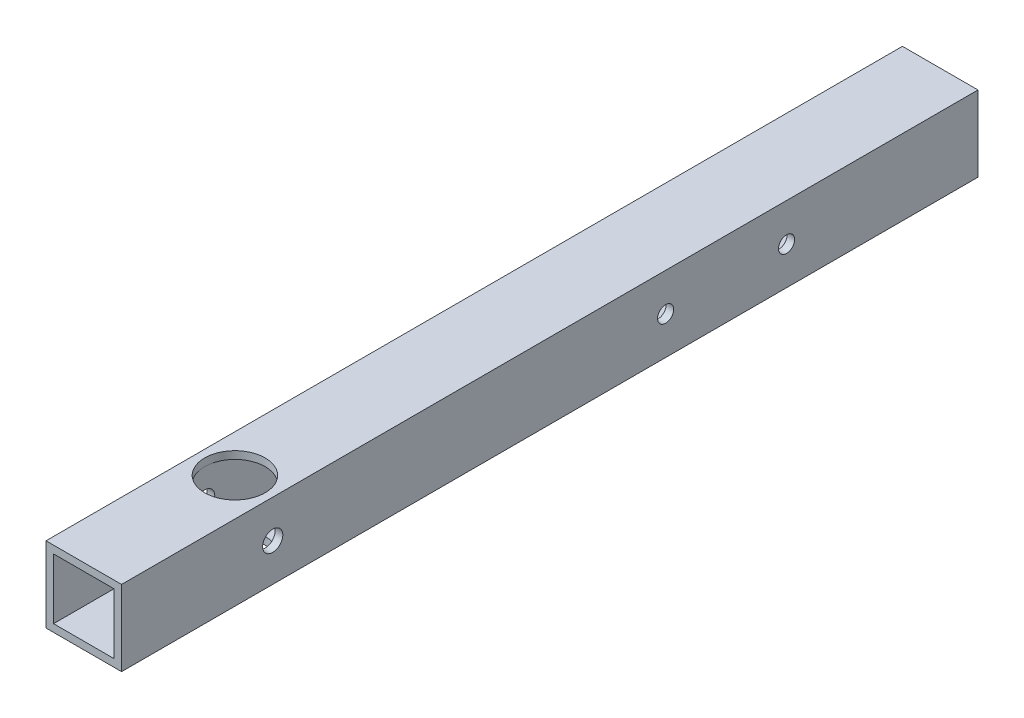
SolidWorks part; units mm, degrees
ref_plane "正面" through (0, 0, 0) normal (0, 0, 1) x (1, 0, 0)
ref_plane "平面" through (0, 0, 0) normal (0, 1, 0) x (1, 0, 0)
ref_plane "右側面" through (0, 0, 0) normal (1, 0, 0) x (0, 0, -1)
sketch "ｽｹｯﾁ1" plane through (0, 0, 0) normal (0, 0, 1) x (1, 0, 0)
  line L1 (-7.5, -7.5) -> (7.5, -7.5)
  line L2 (-7.5, -7.5) -> (-7.5, 7.5)
  line L3 (-7.5, 7.5) -> (7.5, 7.5)
  line L4 (7.5, -7.5) -> (7.5, 7.5)
  line L5 (-7.5, -7.5) -> (7.5, 7.5) construction
  line L6 (-7.5, 7.5) -> (7.5, -7.5) construction
  point P0 (0, 0)
  dimension "D1" = 15
extrude "押し出し-薄板1" add sketch "ｽｹｯﾁ1" along normal blind 160 thin thin type one direction reverse wall 1.5
sketch "ｽｹｯﾁ3" plane through (0, -7.5, 0) normal (0, -1, 0) x (1, 0, 0)
  line L0 (0, 160) -> (0, 0) construction
  line L1 (-7.5, 160) -> (7.5, 160) construction
  line L3 (0, 80) -> (50000, 80) construction
  line L4 (7.5, 160) -> (7.5, 0) construction
  circle A4 centre (0, 140) radius 6
  point P17 (0, 80)
  point P20 (7.5, 80)
  dimension "D3" = 20
  dimension "D5" = 12
extrude "ｶｯﾄ - 押し出し3" cut sketch "ｽｹｯﾁ3" against normal through all
sketch "ｽｹｯﾁ7" plane through (-7.5, 0, 0) normal (-1, 0, 0) x (0, 0, 1)
  line L0 (140, 7.5) -> (140, -7.5) construction
  line L1 (160, 7.5) -> (0, 7.5) construction
  line L2 (160, -7.5) -> (0, -7.5) construction
  line L3 (160, 7.5) -> (160, -7.5) construction
  circle A0 centre (140, 0) radius 2
  dimension "D2" = 4
  dimension "D1" = 20
extrude "ｶｯﾄ - 押し出し4" cut sketch "ｽｹｯﾁ7" against normal through all
sketch "ｽｹｯﾁ12" plane through (7.5, 0, 0) normal (1, 0, 0) x (0, 0, -1)
  line L0 (0, -7.5) -> (0, 7.5) construction
  line L1 (0, 0) -> (-160, 0) construction
  line L3 (-160, -7.5) -> (-160, 7.5) construction
  circle A4 centre (-38, 0) radius 1.6
  circle A13 centre (-62, 0) radius 1.6
  dimension "D1" = 38
  dimension "D2" = 3.2
  dimension "D5" = 24
extrude "ｶｯﾄ - 押し出し5" cut sketch "ｽｹｯﾁ12" against normal through all and the other way through all
sketch "ｽｹｯﾁ13" plane through (0, 0, 160) normal (0, 0, 1) x (1, 0, 0)
  line L0 (7.5, -7.5) -> (7.5, 7.5) construction
  line L1 (-6, -6) -> (6, -6)
  line L2 (-6, -6) -> (-6, 6)
  line L3 (-6, 6) -> (6, 6)
  line L4 (6, -6) -> (6, 6)
  line L5 (-6, -6) -> (6, 6) construction
  line L6 (-6, 6) -> (6, -6) construction
  line L7 (-7.5, -7.5) -> (7.5, -7.5)
  line L8 (-7.5, -7.5) -> (-7.5, 7.5)
  line L9 (-7.5, 7.5) -> (7.5, 7.5)
  line L10 (7.5, -7.5) -> (7.5, 7.5)
  line L11 (-7.5, -7.5) -> (7.5, 7.5) construction
  line L12 (-7.5, 7.5) -> (7.5, -7.5) construction
  line L13 (7.5, 7.5) -> (-7.5, 7.5) construction
  point P0 (0, 0)
  point P7 (0, 0)
extrude "ﾎﾞｽ - 押し出し1" add sketch "ｽｹｯﾁ13" along normal blind 10
